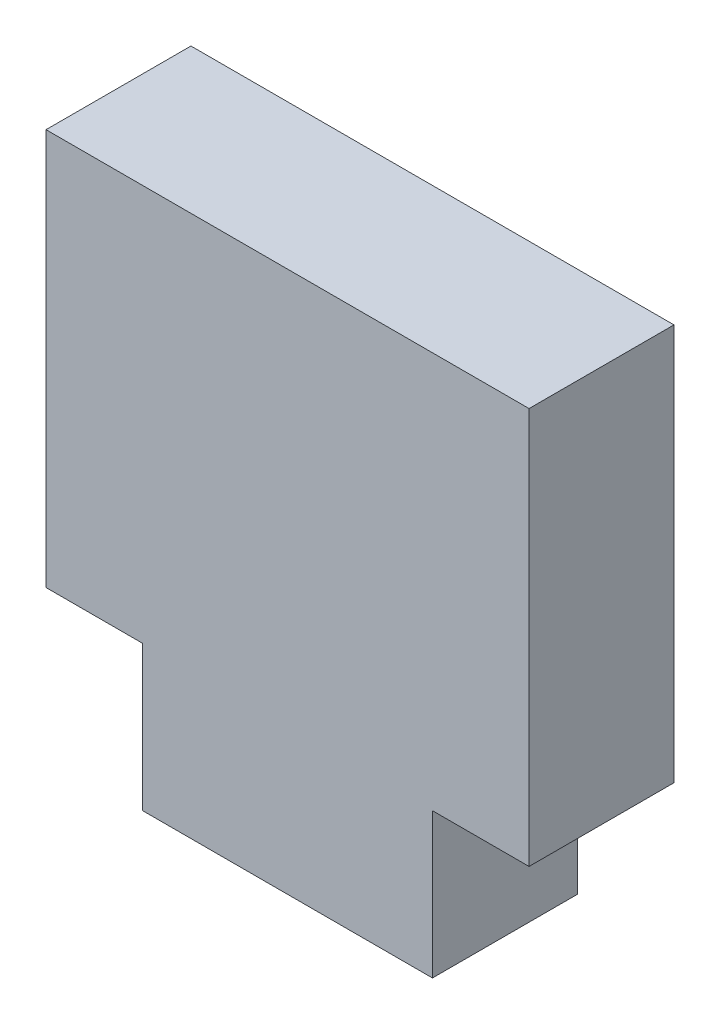
SolidWorks part; units mm, degrees
ref_plane "Front Plane" through (0, 0, 0) normal (0, 0, 1) x (1, 0, 0)
ref_plane "Top Plane" through (0, 0, 0) normal (0, 1, 0) x (1, 0, 0)
ref_plane "Right Plane" through (0, 0, 0) normal (1, 0, 0) x (0, 0, -1)
sketch "Sketch1" plane through (0, 0, 0) normal (0, 0, 1) x (1, 0, 0)
  line L1 (-5, -4.105) -> (5, -4.105)
  line L2 (-5, -4.105) -> (-5, 4.105)
  line L3 (-5, 4.105) -> (5, 4.105)
  line L4 (5, -4.105) -> (5, 4.105)
  line L5 (-5, -4.105) -> (5, 4.105) construction
  line L6 (-5, 4.105) -> (5, -4.105) construction
  line L7 (-3, -4.105) -> (3, -4.105)
  line L8 (-3, -4.105) -> (-3, -7.105)
  line L9 (-3, -7.105) -> (3, -7.105)
  line L10 (3, -4.105) -> (3, -7.105)
  point P0 (0, 0)
  point P10 (0, -7.105)
  point P11 (0, -4.105)
  dimension "D1" = 8.21
  dimension "D2" = 10
  dimension "D3" = 6
  dimension "D4" = 3
  dimension "D5" = 0
extrude "Boss-Extrude1" add sketch "Sketch1" along normal blind 3 contours L1 L4 L3 L2 | L10 L1 L8 L9
